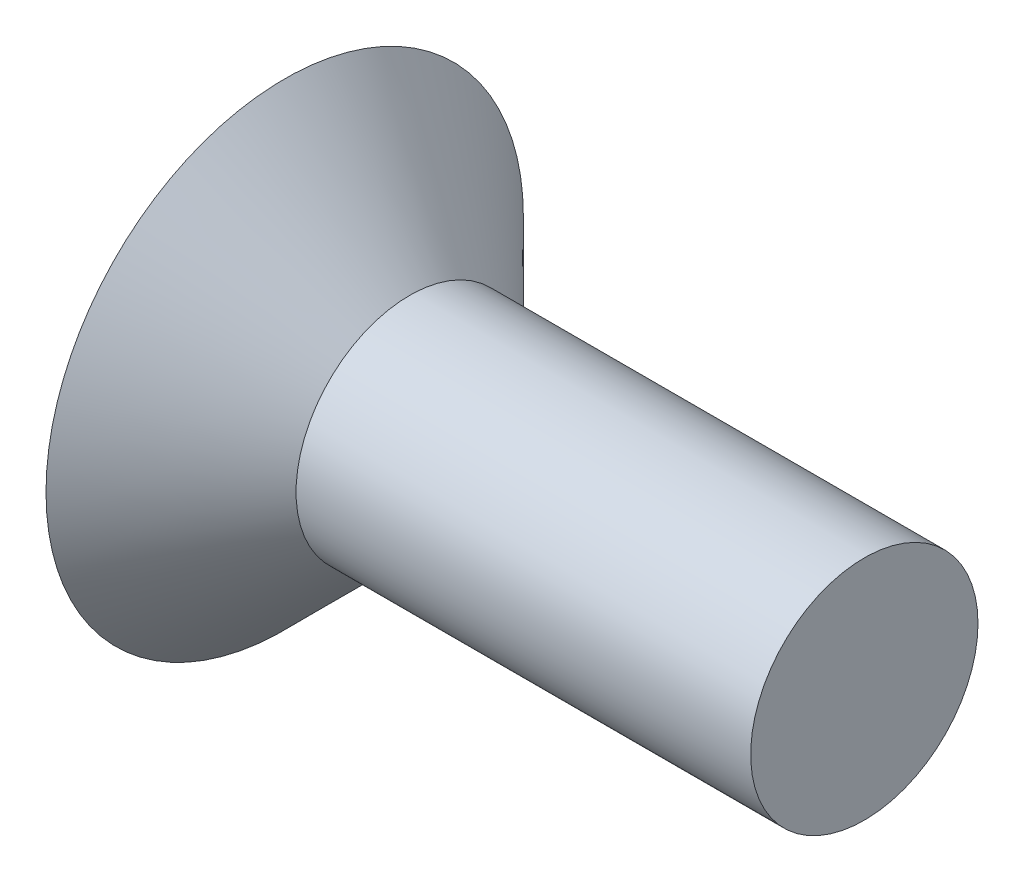
SolidWorks part; units mm, degrees
ref_plane "Спереди" through (0, 0, 0) normal (0, 0, 1) x (1, 0, 0)
ref_plane "Сверху" through (0, 0, 0) normal (0, 1, 0) x (1, 0, 0)
ref_plane "Справа" through (0, 0, 0) normal (1, 0, 0) x (0, 0, -1)
sketch "Эскиз1" plane through (0, 0, 0) normal (0, 0, 1) x (1, 0, 0)
  line L0 (0, 0) -> (0, 3.15)
  line L1 (0, 3.15) -> (1.65, 1.5)
  line L2 (1.65, 1.5) -> (7.65, 1.5)
  line L3 (7.65, 1.5) -> (7.65, 0)
  line L4 (7.65, 0) -> (0, 0)
  line L5 (0, 0) -> (-2.697, 0) construction
  dimension "D1" = 3
  dimension "D2" = 45
  dimension "D3" = 1.65
  dimension "D4" = 6
revolve "Повернуть1" add sketch "Эскиз1" angle 360 about L5
cosmetic thread "Условное изображение резьбы1" parameters "D1"=5, "D2"=2
